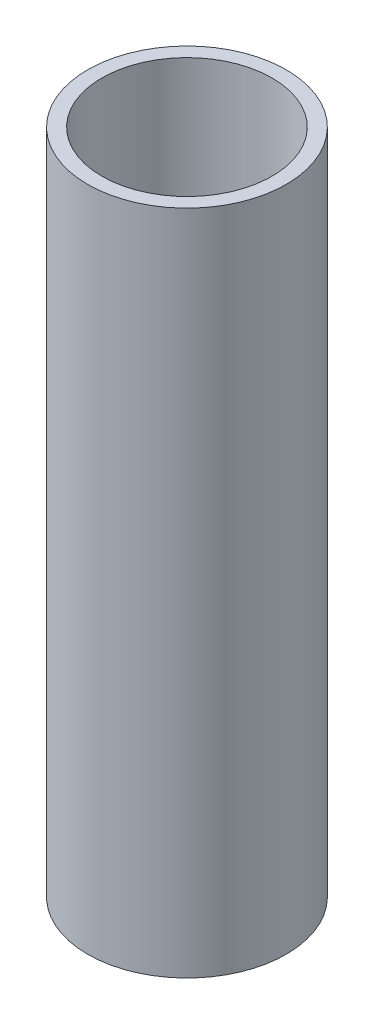
SolidWorks part; units mm, degrees
material "Acrylic (Medium-high impact)"
ref_plane "Front Plane" through (0, 0, 0) normal (0, 0, 1) x (1, 0, 0)
ref_plane "Top Plane" through (0, 0, 0) normal (0, 1, 0) x (1, 0, 0)
ref_plane "Right Plane" through (0, 0, 0) normal (1, 0, 0) x (0, 0, -1)
sketch "Sketch1" plane through (0, 0, 0) normal (0, 1, 0) x (1, 0, 0)
  circle A0 centre (0, 0) radius 44.45
  circle A1 centre (0, 0) radius 38.1
  dimension "D1" = 76.2
  dimension "D2" = 6.35
extrude "Boss-Extrude1" add sketch "Sketch1" along normal blind 298.45
